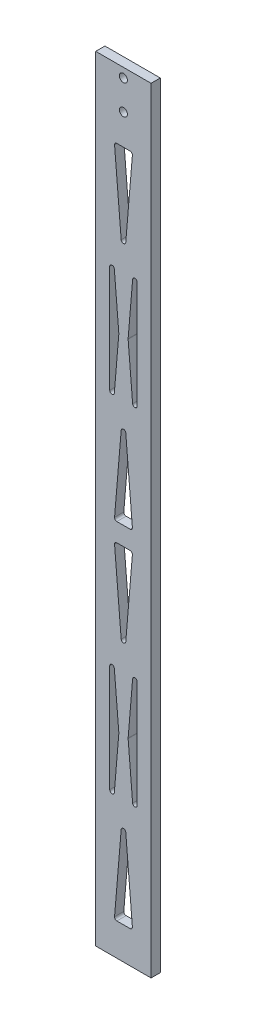
SolidWorks part; units mm, degrees
ref_plane "Front Plane" through (0, 0, 0) normal (0, 0, 1) x (1, 0, 0)
ref_plane "Top Plane" through (0, 0, 0) normal (0, 1, 0) x (1, 0, 0)
ref_plane "Right Plane" through (0, 0, 0) normal (1, 0, 0) x (0, 0, -1)
sketch "Sketch1" plane through (0, 0, 0) normal (0, 0, 1) x (1, 0, 0)
  line L1 (-25.4, -292.1) -> (-25.4, 241.3) construction
  line L2 (-25.4, 241.3) -> (12.7, 241.3)
  line L3 (-25.4, 241.3) -> (-25.4, -292.1)
  line L4 (-25.4, -292.1) -> (12.7, -292.1)
  line L5 (12.7, 241.3) -> (12.7, -292.1)
  point P6 (-25.4, -25.4)
  dimension "D1" = 533.4
  dimension "D2" = 38.1
  dimension "D3" = 12.7
  dimension "D4" = 241.3
extrude "Boss-Extrude1" add sketch "Sketch1" along normal mid plane 6.35
sketch "Sketch2" plane through (0, 0, 3.175) normal (0, 0, 1) x (1, 0, 0)
  line L0 (12.7, 241.3) -> (-25.4, 241.3) construction
  line L1 (-6.35, 241.3) -> (-6.35, 205.7623) construction
  circle A0 centre (-6.35, 234.95) radius 2.7781
  circle A1 centre (-6.35, 214.63) radius 2.7781
  point P8 (0, 0)
  dimension "D3" = 5.5562
  dimension "D1" = 6.35
  dimension "D2" = 20.32
extrude "Cut-Extrude1" cut sketch "Sketch2" against normal through all
sketch "Sketch3" plane through (0, 0, 3.175) normal (0, 0, 1) x (1, 0, 0)
  line L0 (12.7, -292.1) -> (12.7, 241.3) construction
  line L1 (12.7, 203.2) -> (-25.2838, 203.2)
  line L2 (12.7, 203.2) -> (12.7, -279.3892)
  line L3 (12.7, -279.3892) -> (-25.2838, -279.3892)
  line L4 (-25.2838, 203.2) -> (-25.2838, -279.3892)
  line L5 (12.7, 241.3) -> (-25.4, 241.3) construction
  line L6 (-25.4, -292.1) -> (12.7, -292.1) construction
  line L7 (3.175, 193.675) -> (-15.7588, 193.675)
  line L8 (-15.7588, 193.675) -> (-15.7588, -269.8642)
  line L9 (3.175, -269.8642) -> (-15.7588, -269.8642)
  line L10 (3.175, 193.675) -> (3.175, -269.8642)
  line L11 (3.175, -38.0946) -> (-15.7588, -38.0946) construction
  line L14 (3.175, -31.7446) -> (-15.7588, -31.7446)
  line L17 (3.175, -44.4446) -> (-15.7588, -44.4446)
  line L20 (3.175, 193.675) -> (-15.7588, -31.7446) construction
  line L23 (6.3389, 193.4093) -> (-12.5949, -32.0104)
  line L26 (0.0111, 193.9407) -> (-18.9226, -31.4789)
  line L27 (-15.7588, 193.675) -> (3.175, -31.7446) construction
  line L28 (-12.5949, 193.9407) -> (6.3389, -31.4789)
  line L29 (-18.9226, 193.4093) -> (0.0111, -32.0104)
  line L30 (3.175, -269.8642) -> (-15.7588, -44.4446) construction
  line L31 (6.3389, -269.5985) -> (-12.5949, -44.1789)
  line L32 (0.0111, -270.13) -> (-18.9226, -44.7104)
  line L33 (-15.7588, -269.8642) -> (3.175, -44.4446) construction
  line L34 (-12.5949, -270.13) -> (6.3389, -44.7104)
  line L35 (-18.9226, -269.5985) -> (0.0111, -44.1789)
  arc A10 (6.3389, 193.4093) -> (0.0111, 193.9407) centre (3.175, 193.675) ccw
  arc A11 (-18.9226, -31.4789) -> (-12.5949, -32.0104) centre (-15.7588, -31.7446) ccw
  arc A12 (-12.5949, 193.9407) -> (-18.9226, 193.4093) centre (-15.7588, 193.675) ccw
  arc A13 (0.0111, -32.0104) -> (6.3389, -31.4789) centre (3.175, -31.7446) ccw
  arc A14 (6.3389, -269.5985) -> (0.0111, -270.13) centre (3.175, -269.8642) cw
  arc A15 (-18.9226, -44.7104) -> (-12.5949, -44.1789) centre (-15.7588, -44.4446) cw
  arc A16 (-12.5949, -270.13) -> (-18.9226, -269.5985) centre (-15.7588, -269.8642) cw
  arc A17 (0.0111, -44.1789) -> (6.3389, -44.7104) centre (3.175, -44.4446) cw
  point P20 (-6.2919, 80.9652)
  point P25 (-6.2919, 80.9652)
  point P30 (-6.2919, -157.1544)
  point P35 (-6.2919, -157.1544)
  dimension "D5" = 12.7
  dimension "D6" = 3.175
  dimension "D1" = 37.9838
  dimension "D2" = 38.1
  dimension "D3" = 12.7108
  dimension "D4" = 9.525
extrude "Cut-Extrude2" cut sketch "Sketch3" against normal through all contours L7 L28 L26 | L23 L28 L10 | L29 L8 L26 | L29 L23 L14 | L31 L35 L17 | L34 L31 L10 | L8 L35 L32 | L34 L9 L32
fillet "Fillet1" radius 1.5875 24 edges at (3.175, -82.3783, 0) (-12.5726, -44.4446, 0) (-0.0112, -44.4446, 0) (-6.2919, -119.2207, 0) (-9.4781, 80.9652, 0) (-15.7588, 6.1891, 0) (-15.7588, 155.7413, 0) (3.175, 6.1891, 0) (-3.1057, 80.9652, 0) (3.175, 155.7413, 0) (3.175, -231.9305, 0) (-3.1057, -157.1544, 0) (-12.5726, 193.675, 0) (-0.0112, 193.675, 0) (-9.4781, -157.1544, 0) (-15.7588, -231.9305, 0) (-15.7588, -82.3783, 0) (-6.2919, -195.0881, 0) (-0.0112, -269.8642, 0) (-12.5726, -269.8642, 0) (-0.0112, -31.7446, 0) (-12.5726, -31.7446, 0) (-6.2919, 43.0315, 0) (-6.2919, 118.8989, 0)
move or copy body "Body-Move/Copy1" [suppressed] bodies to move or copy 102 parameters "D1"=0, "D2"=0, "D3"=0
